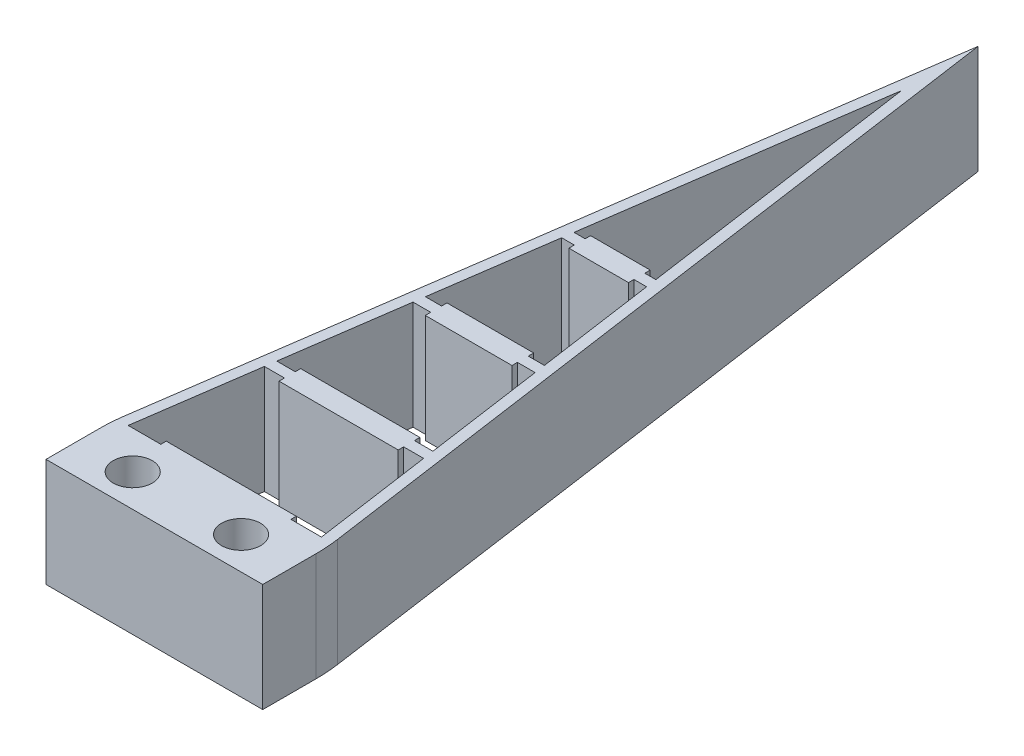
SolidWorks part; units mm, degrees
ref_plane "Front Plane" through (0, 0, 0) normal (0, 0, 1) x (1, 0, 0)
ref_plane "Top Plane" through (0, 0, 0) normal (0, 1, 0) x (1, 0, 0)
ref_plane "Right Plane" through (0, 0, 0) normal (1, 0, 0) x (0, 0, -1)
sketch "Sketch1" plane through (0, 0, 0) normal (0, 1, 0) x (1, 0, 0)
  line L1 (10, 0) -> (0, 70)
  line L2 (0, 70) -> (-10, 0)
  line L5 (0, 0) -> (0, 70) construction
  line L37 (0, 62.9289) -> (-3.3469, 39.5004)
  line L39 (0, 62.9289) -> (3.3476, 39.496)
  line L42 (-7.347, 11.5) -> (-5.5, 11.5)
  line L43 (-7.2041, 12.5) -> (-5.5, 12.5)
  line L44 (-5.5, 12.5) -> (-5.5, 13)
  line L45 (-5.5, 11) -> (5.5, 11)
  line L46 (-5.5, 11) -> (-5.5, 11.5)
  line L47 (-5.5, 13) -> (5.5, 13)
  line L48 (5.5, 11) -> (5.5, 11.5)
  line L49 (-5.5, 11) -> (5.5, 13) construction
  line L50 (-5.5, 13) -> (5.5, 11) construction
  line L51 (5.5, 12.5) -> (5.5, 13)
  line L52 (5.5, 12.5) -> (7.2041, 12.5)
  line L53 (5.5, 11.5) -> (7.347, 11.5)
  line L54 (-7.347, 11.5) -> (-8.9184, 0.5)
  line L55 (7.347, 11.5) -> (8.9184, 0.5)
  line L56 (-5.6327, 23.5) -> (-4, 23.5)
  line L57 (-5.4898, 24.5) -> (-4, 24.5)
  line L58 (-5.6327, 23.5) -> (-7.2041, 12.5)
  line L59 (-4, 23) -> (4, 23)
  line L60 (-4, 23) -> (-4, 23.5)
  line L61 (-4, 25) -> (4, 25)
  line L62 (4, 23) -> (4, 23.5)
  line L63 (-4, 23) -> (4, 25) construction
  line L64 (-4, 25) -> (4, 23) construction
  line L65 (-4, 24.5) -> (-4, 25)
  line L66 (4, 24.5) -> (4, 25)
  line L67 (4, 24.5) -> (5.4898, 24.5)
  line L68 (4, 23.5) -> (5.6327, 23.5)
  line L69 (5.6327, 23.5) -> (7.2041, 12.5)
  line L70 (-3.9184, 35.5) -> (-2.75, 35.5)
  line L71 (-3.7756, 36.5) -> (-2.75, 36.5)
  line L72 (-3.9184, 35.5) -> (-5.4898, 24.5)
  line L73 (-2.75, 35) -> (2.75, 35)
  line L74 (-2.75, 35) -> (-2.75, 35.5)
  line L75 (-2.75, 37) -> (2.75, 37)
  line L76 (2.75, 35) -> (2.75, 35.5)
  line L77 (-2.75, 35) -> (2.75, 37) construction
  line L78 (-2.75, 37) -> (2.75, 35) construction
  line L79 (-2.75, 36.5) -> (-2.75, 37)
  line L80 (3.9184, 35.5) -> (5.4898, 24.5)
  line L81 (2.75, 36.5) -> (3.7756, 36.5)
  line L82 (2.75, 35.5) -> (3.9184, 35.5)
  line L83 (2.75, 36.5) -> (2.75, 37)
  line L86 (-3.3469, 39.5004) -> (-3.7756, 36.5)
  line L91 (-5.5, 12.5) -> (-5.5, 11.5) construction
  line L92 (-4, 24.5) -> (-4, 23.5) construction
  line L97 (3.3476, 39.496) -> (3.7756, 36.5)
  line L98 (-8.9184, 0.5) -> (-5.904, 0.5)
  line L100 (-5.904, 0.5) -> (-5.904, 1)
  line L101 (-5.904, 1) -> (6.096, 1)
  line L102 (6.096, 0.5) -> (6.096, 1)
  line L103 (-6.3877, -1.0479) -> (6.096, 1) construction
  line L104 (-5.904, 1) -> (5.956, -1.0088) construction
  line L105 (6.096, 0.5) -> (8.9184, 0.5)
  line L112 (-10, 0) -> (-10, -6)
  line L113 (10, 0) -> (10, -6)
  line L114 (-10, -6) -> (10, -6)
  line L115 (-2.75, 36.5) -> (-2.75, 35.5) construction
  line L116 (-10, 0) -> (10, 0) construction
  line L117 (-5, -3) -> (5, -3) construction
  circle A0 centre (-5, -3) radius 1.8
  circle A1 centre (5, -3) radius 1.8
  point P12 (0, 12)
  point P25 (0, 24)
  point P38 (0, 36)
  point P45 (-5.5, 12)
  point P47 (-4, 24)
  point P50 (-2.75, 36)
  point P51 (0, -3)
  point P73 (0, -6)
  dimension "D5" = 11
  dimension "D7" = 1
  dimension "D6" = 20
  dimension "D8" = 2
  dimension "D9" = 8
  dimension "D10" = 10
  dimension "D13" = 1
  dimension "D14" = 70
  dimension "D16" = 2
  dimension "D17" = 1
  dimension "D30" = 3.6
  dimension "D31" = 3.6
  dimension "D3" = 1
  dimension "D4" = 2
  dimension "D11" = 12
  dimension "D12" = 12
  dimension "D15" = 5.5
  dimension "D18" = 12
  dimension "D19" = 0.5
  dimension "D20" = 0.5
  dimension "D22" = 6
  dimension "D23" = 12
  dimension "D25" = 3
extrude "Boss-Extrude1" add sketch "Sketch1" along normal mid plane 10
fillet "Fillet1" radius 15 2 edges at (10, 0, 0) (-10, 0, 0)
